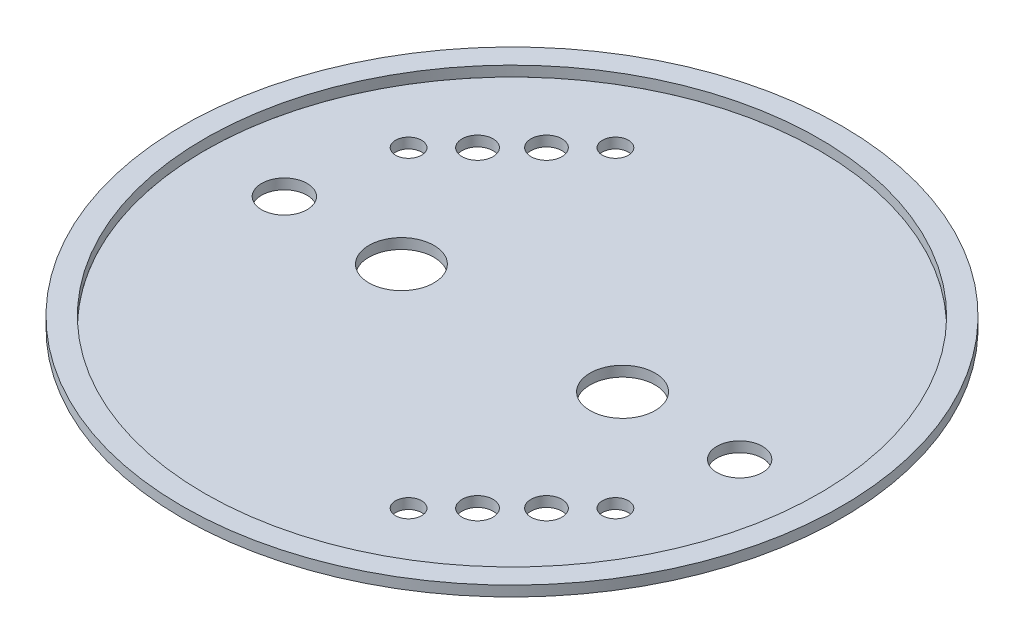
SolidWorks part; units mm, degrees
ref_plane "Front Plane" through (0, 0, 0) normal (0, 0, 1) x (1, 0, 0)
ref_plane "Top Plane" through (0, 0, 0) normal (0, 1, 0) x (1, 0, 0)
ref_plane "Right Plane" through (0, 0, 0) normal (1, 0, 0) x (0, 0, -1)
sketch "Sketch1" plane through (0, 0, 0) normal (0, 1, 0) x (1, 0, 0)
  circle A0 centre (0, 0) radius 76
extrude "Boss-Extrude1" add sketch "Sketch1" along normal blind 15
sketch "Sketch2" plane through (0, 15, 0) normal (0, 1, 0) x (1, 0, 0)
  circle A0 centre (0, 0) radius 70.875
  point P3 (0, 0)
extrude "Cut-Extrude1" cut sketch "Sketch2" against normal blind 7.5
sketch "Sketch3" plane through (0, 0, 0) normal (0, -1, 0) x (-1, 0, 0)
  circle A0 centre (0, 0) radius 70.875
  circle A1 centre (0, 0) radius 74.25
extrude "Cut-Extrude2" cut sketch "Sketch3" against normal blind 7.5
sketch "Sketch4" plane through (0, 7.5, 0) normal (0, 1, 0) x (1, 0, 0)
  circle A0 centre (-25.5, 0) radius 7.5
  circle A1 centre (-52.5, 0) radius 5.25
  circle A2 centre (25.5, 0) radius 7.5
  circle A3 centre (52.5, 0) radius 5.25
  circle A4 centre (-32.025, 39.975) radius 3.57
  circle A5 centre (-39.975, 32.025) radius 3.57
  circle A6 centre (-47.925, 24.075) radius 3
  circle A7 centre (-24.075, 47.925) radius 3
  circle A8 centre (32.025, -39.975) radius 3.57
  circle A9 centre (39.975, -32.025) radius 3.57
  circle A10 centre (47.925, -24.075) radius 3
  circle A11 centre (24.075, -47.925) radius 3
extrude "Cut-Extrude3" cut sketch "Sketch4" against normal blind 7.5
sketch "Sketch10" plane through (0, 0, 0) normal (0, -1, 0) x (1, 0, 0)
  circle A0 centre (0, 0) radius 74.0359
  circle A1 centre (0, 0) radius 76
extrude "Cut-Extrude6" cut sketch "Sketch10" against normal blind 7.5
sketch "Sketch12" plane through (0, 15, 0) normal (0, 1, 0) x (1, 0, 0)
  circle A0 centre (0, 0) radius 76
extrude "Cut-Extrude8" cut sketch "Sketch12" against normal blind 5.12
sketch "Sketch13" plane through (0, 0, 0) normal (0, -1, 0) x (1, 0, 0)
  circle A0 centre (0, 0) radius 70.875
extrude "Cut-Extrude9" cut sketch "Sketch13" against normal blind 5.12
